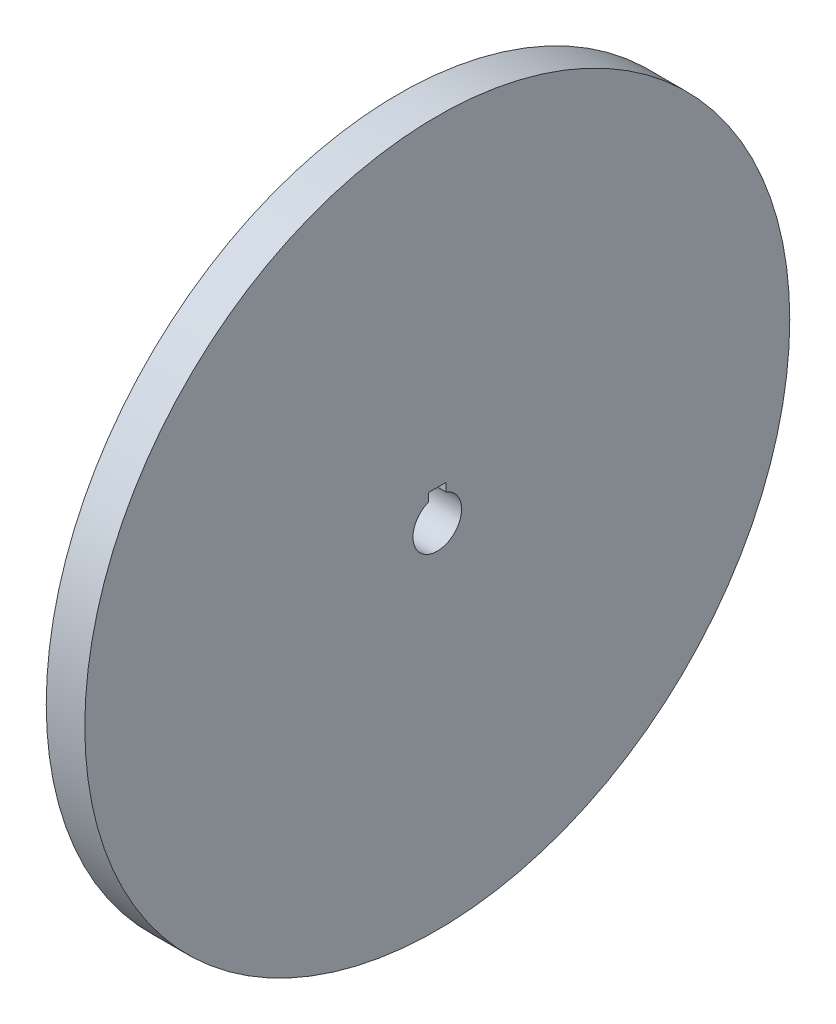
SolidWorks part; units mm, degrees
material "Gray Cast Iron"
ref_plane "Front Plane" through (0, 0, 0) normal (0, 0, 1) x (1, 0, 0)
ref_plane "Top Plane" through (0, 0, 0) normal (0, 1, 0) x (1, 0, 0)
ref_plane "Right Plane" through (0, 0, 0) normal (1, 0, 0) x (0, 0, -1)
sketch "Sketch1" plane through (0, 0, 0) normal (1, 0, 0) x (0, 0, -1)
  line L0 (-2.5, 3.9) -> (2.5, 3.9) construction
  line L2 (-2.5, 6.5383) -> (-2.5, 8.9)
  line L3 (-2.5, 8.9) -> (2.5, 8.9)
  line L4 (2.5, 6.5383) -> (2.5, 8.9)
  line L5 (-2.5, 3.9) -> (2.5, 8.9) construction
  line L6 (-2.5, 8.9) -> (2.5, 3.9) construction
  line L7 (2.5, 3.9) -> (2.5, 6.5383) construction
  line L8 (-2.5, 3.9) -> (-2.5, 6.5383) construction
  arc A0 (-2.5, 6.5383) -> (2.5, 6.5383) centre (0, 0) ccw
  circle A1 centre (0, 0) radius 101.6
  point P4 (0, 6.4)
  point P9 (2.486, 6.5383)
  point P12 (2.3301, 6.6008)
  dimension "D1" = 14
  dimension "D2" = 203.2
  dimension "D3" = 5
  dimension "D4" = 3.1
  dimension "D5" = 5
extrude "Boss-Extrude1" add sketch "Sketch1" along normal mid plane 11.1125
